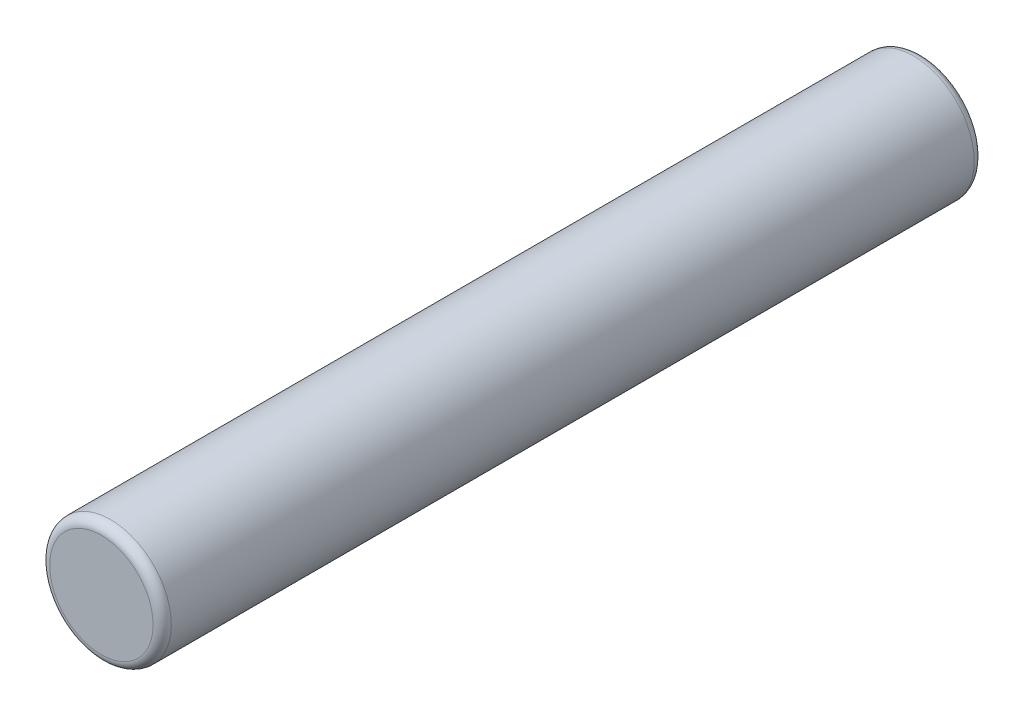
SolidWorks part; units mm, degrees
ref_plane "Front Plane" through (0, 0, 0) normal (0, 0, 1) x (1, 0, 0)
ref_plane "Top Plane" through (0, 0, 0) normal (0, 1, 0) x (1, 0, 0)
ref_plane "Right Plane" through (0, 0, 0) normal (1, 0, 0) x (0, 0, -1)
sketch "Sketch1" plane through (0, 0, 0) normal (0, 0, 1) x (1, 0, 0)
  circle A0 centre (0, 0) radius 20
  dimension "D1" = 40
extrude "Boss-Extrude1" add sketch "Sketch1" along normal mid plane 270
fillet "Fillet1" radius 3 2 edges at (20, 0, -135) (20, 0, 135)
